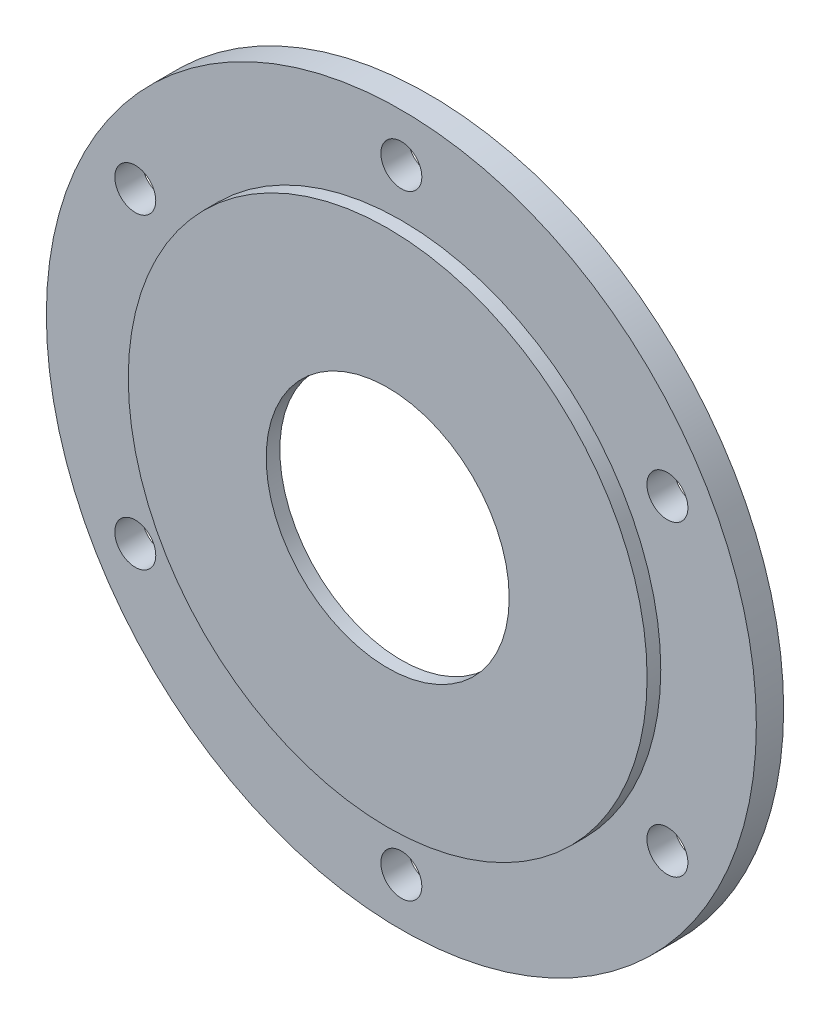
SolidWorks part; units mm, degrees
material "Resina de melamina"
ref_plane "Alzado" through (0, 0, 0) normal (0, 0, 1) x (1, 0, 0)
ref_plane "Planta" through (0, 0, 0) normal (0, 1, 0) x (1, 0, 0)
ref_plane "Vista lateral" through (0, 0, 0) normal (1, 0, 0) x (0, 0, -1)
sketch "Croquis1" plane through (0, 0, 0) normal (0, 0, 1) x (1, 0, 0)
  circle A0 centre (0, 0) radius 8.9
  circle A1 centre (0, 0) radius 19
  dimension "D1" = 17.8
  dimension "D2" = 38
extrude "Saliente-Extruir1" add sketch "Croquis1" along normal blind 1
sketch "Croquis2" plane through (0, 0, 0) normal (0, 0, -1) x (-1, 0, 0)
  circle A0 centre (0, 0) radius 19
  circle A1 centre (0, 0) radius 26
  dimension "D1" = 52
extrude "Saliente-Extruir2" add sketch "Croquis2" along normal blind 2 separate body
sketch "Croquis3" plane through (0, 0, 0) normal (0, 0, 1) x (1, 0, 0)
  line L0 (0, 0) -> (0, 22.5) construction
  line L1 (0, 22.5) -> (0, 26) construction
  line L2 (0, 22.5) -> (0, 18.876) construction
  circle A0 centre (0, 22.5) radius 1.5
  circle A1 centre (0, 0) radius 26 construction
  circle A2 centre (19.4856, 11.25) radius 1.5
  circle A3 centre (19.4856, -11.25) radius 1.5
  circle A4 centre (0, -22.5) radius 1.5
  circle A5 centre (-19.4856, -11.25) radius 1.5
  circle A6 centre (-19.4856, 11.25) radius 1.5
  dimension "D3" = 3
  dimension "D1" = 22.5
  dimension "D2" = 6
extrude "Cortar-Extruir1" cut sketch "Croquis3" against normal blind 3
